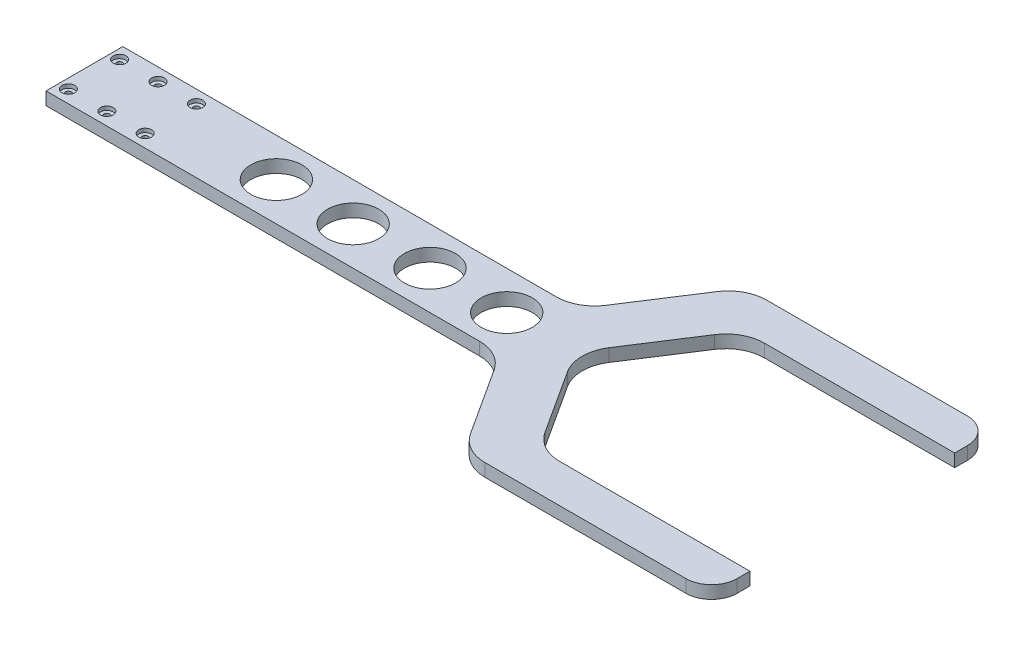
SolidWorks part; units mm, degrees
ref_plane "정면" through (0, 0, 0) normal (0, 0, 1) x (1, 0, 0)
ref_plane "윗면" through (0, 0, 0) normal (0, 1, 0) x (1, 0, 0)
ref_plane "우측면" through (0, 0, 0) normal (1, 0, 0) x (0, 0, -1)
sketch "스케치1" plane through (0, 0, 0) normal (0, 1, 0) x (1, 0, 0)
  line L0 (363.8664, 43.7016) -> (397.9023, 96.2984)
  line L1 (0, 0) -> (383.2312, 0) construction
  line L2 (0, -30) -> (0, 30)
  line L3 (0, 30) -> (338.6799, 30)
  line L5 (423.0889, 110) -> (580, 110)
  line L6 (600, 90) -> (600, 80)
  line L7 (600, 80) -> (451.3201, 80)
  line L8 (426.1336, 66.2984) -> (393.7781, 16.2984)
  line L9 (426.1336, -66.2984) -> (393.7781, -16.2984)
  line L10 (600, -80) -> (451.3201, -80)
  line L11 (600, -90) -> (600, -80)
  line L12 (423.0889, -110) -> (580, -110)
  line L13 (0, -30) -> (338.6799, -30)
  line L14 (363.8664, -43.7016) -> (397.9023, -96.2984)
  arc A0 (451.3201, 80) -> (426.1336, 66.2984) centre (451.3201, 50) ccw
  arc A1 (397.9023, 96.2984) -> (423.0889, 110) centre (423.0889, 80) cw
  arc A2 (338.6799, 30) -> (363.8664, 43.7016) centre (338.6799, 60) ccw
  arc A3 (580, 110) -> (600, 90) centre (580, 90) cw
  arc A4 (580, -110) -> (600, -90) centre (580, -90) ccw
  arc A5 (338.6799, -30) -> (363.8664, -43.7016) centre (338.6799, -60) cw
  arc A6 (397.9023, -96.2984) -> (423.0889, -110) centre (423.0889, -80) ccw
  arc A7 (451.3201, -80) -> (426.1336, -66.2984) centre (451.3201, -50) cw
  arc A8 (393.7781, -16.2984) -> (393.7781, 16.2984) centre (418.9646, 0) cw
  point P20 (435, 80)
  point P25 (355, 30)
  point P28 (600, 110)
  dimension "D8" = 30
  dimension "D9" = 20
  dimension "D10" = 30
  dimension "D1" = 60
  dimension "D2" = 600
  dimension "D3" = 30
  dimension "D4" = 160
  dimension "D5" = 40
  dimension "D6" = 355
  dimension "D7" = 435
extrude "보스-돌출1" add sketch "스케치1" along normal blind 10
sketch "스케치3" plane through (0, 10, 0) normal (0, 1, 0) x (1, 0, 0)
  line L0 (0, 0) -> (600.6831, 0) construction
  line L1 (0, 30) -> (0, -30) construction
  circle A0 centre (150, 0) radius 20
  circle A1 centre (210, 0) radius 20
  circle A2 centre (270, 0) radius 20
  circle A3 centre (330, 0) radius 20
  dimension "D1" = 40
  dimension "D2" = 150
  dimension "D3" = 60
  dimension "D4" = 60
  dimension "D5" = 60
extrude "컷-돌출1" cut sketch "스케치3" against normal through all
sketch "스케치4" plane through (0, 10, 0) normal (0, 1, 0) x (1, 0, 0)
  line L0 (0, -30) -> (338.6799, -30) construction
  line L1 (0, 30) -> (0, -30) construction
  circle A0 centre (7.5, 20) radius 5
  circle A1 centre (37.5, 20) radius 5
  circle A2 centre (67.5, 20) radius 5
  circle A3 centre (7.5, -20) radius 5
  circle A4 centre (37.5, -20) radius 5
  circle A5 centre (67.5, -20) radius 5
  dimension "D1" = 10
  dimension "D2" = 10
  dimension "D3" = 40
  dimension "D4" = 7.5
  dimension "D5" = 30
  dimension "D6" = 30
extrude "컷-돌출2" cut sketch "스케치4" against normal blind 3
sketch "스케치5" plane through (0, 7, 0) normal (0, 1, 0) x (1, 0, 0)
  circle A0 centre (37.5, 20) radius 2.25
  circle A1 centre (67.5, 20) radius 2.25
  circle A2 centre (67.5, -20) radius 2.25
  circle A3 centre (37.5, -20) radius 2.25
  circle A4 centre (7.5, -20) radius 2.25
  circle A5 centre (7.5, 20) radius 2.25
  dimension "D1" = 4.5
extrude "컷-돌출3" cut sketch "스케치5" against normal through all
ref_plane "평면1" through (0, 0, 0) normal (0, 0, -1) x (-1, 0, 0)
